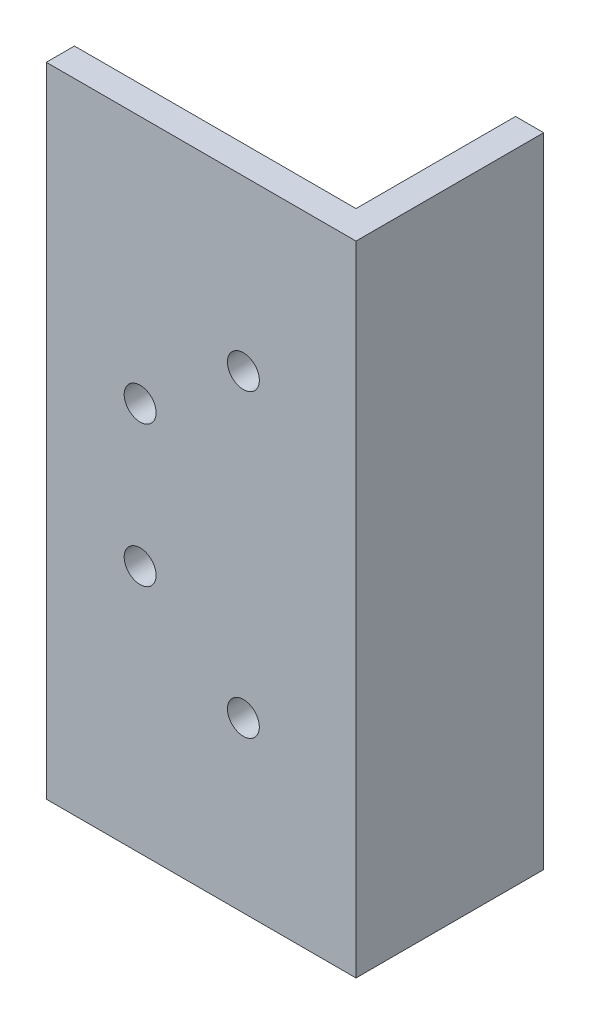
SolidWorks part; units mm, degrees
ref_plane "前视基准面" through (0, 0, 0) normal (0, 0, 1) x (1, 0, 0)
ref_plane "上视基准面" through (0, 0, 0) normal (0, 1, 0) x (1, 0, 0)
ref_plane "右视基准面" through (0, 0, 0) normal (1, 0, 0) x (0, 0, -1)
sketch "草图1" plane through (0, 0, 0) normal (0, 1, 0) x (1, 0, 0)
  line L0 (0, 0) -> (30, 0)
  line L1 (30, 0) -> (33, 0)
  line L2 (0, 3) -> (30, 3)
  line L3 (0, 0) -> (33, 0) construction
  line L4 (0, 0) -> (0, 3)
  line L5 (33, 0) -> (33, 20)
  line L6 (30, 3) -> (30, 0)
  line L7 (33, 20) -> (30, 20)
  line L8 (30, 3) -> (30, 60) construction
  line L9 (33, 0) -> (33, 60) construction
  line L10 (30, 20) -> (30, 3)
  dimension "D2" = 30
  dimension "D3" = 3
  dimension "D4" = 20
  dimension "D1" = 3
extrude "凸台-拉伸1" add sketch "草图1" along normal blind 68 contours L6 L2 L4 L0 | L7 L10 L6 L1 L5
sketch "草图2" plane through (0, 0, 0) normal (0, 0, 1) x (1, 0, 0)
  line L1 (33, 68) -> (33, 0) construction
  line L3 (0, 68) -> (33, 68) construction
  circle A0 centre (21, 18) radius 1.7
  circle A1 centre (21, 50) radius 1.7
  circle A2 centre (10, 26.5) radius 1.7
  circle A3 centre (10, 41.5) radius 1.7
  dimension "D7" = 3.4
  dimension "D1" = 32
  dimension "D2" = 15
  dimension "D3" = 26.5
  dimension "D4" = 18
  dimension "D5" = 12
  dimension "D6" = 11
extrude "切除-拉伸1" cut sketch "草图2" against normal up to next
